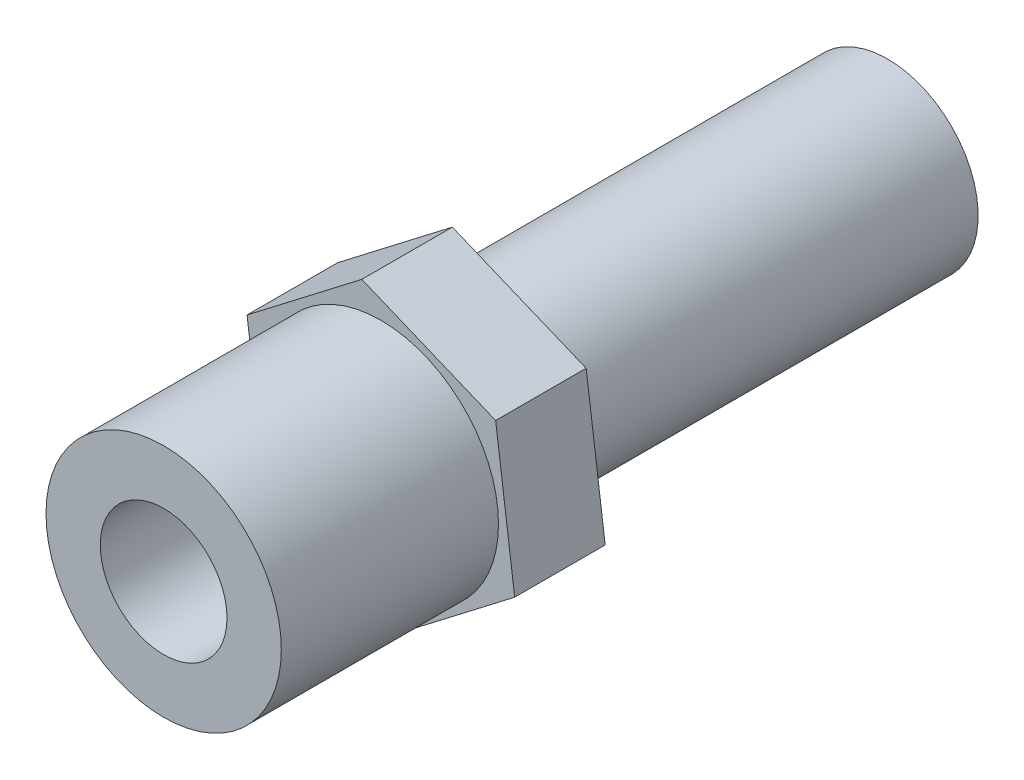
SolidWorks part; units mm, degrees
ref_plane "Front Plane" through (0, 0, 0) normal (0, 0, 1) x (1, 0, 0)
ref_plane "Top Plane" through (0, 0, 0) normal (0, 1, 0) x (1, 0, 0)
ref_plane "Right Plane" through (0, 0, 0) normal (1, 0, 0) x (0, 0, -1)
sketch "Sketch1" plane through (0, 0, 0) normal (0, 0, 1) x (1, 0, 0)
  circle A0 centre (0, 0) radius 6.5
  dimension "D1" = 6.5
extrude "Boss-Extrude1" add sketch "Sketch1" along normal blind 12
sketch "Sketch2" plane through (0, 0, 0) normal (0, 0, -1) x (-1, 0, 0)
  line L1 (-7.3935, -3.0555) -> (-1.0507, -7.9307)
  line L2 (-1.0507, -7.9307) -> (6.3429, -4.8753)
  line L3 (6.3429, -4.8753) -> (7.3935, 3.0555)
  line L4 (7.3935, 3.0555) -> (1.0507, 7.9307)
  line L5 (1.0507, 7.9307) -> (-6.3429, 4.8753)
  line L6 (-6.3429, 4.8753) -> (-7.3935, -3.0555)
  circle A0 centre (0, 0) radius 6.9282 construction
  dimension "D1" = 8
extrude "Boss-Extrude2" add sketch "Sketch2" along normal blind 5 contours L1 L2 L3 L4 L5 L6
sketch "Sketch3" plane through (0, 0, -5) normal (0, 0, -1) x (-1, 0, 0)
  line L0 (-7.3935, -3.0555) -> (7.3935, 3.0555)
  circle A0 centre (0, 0) radius 5
  dimension "D2" = 5
  dimension "D1" = 16
extrude "Boss-Extrude3" add sketch "Sketch3" along normal blind 23 contours L0 A0 | L0 A0
sketch "Sketch4" plane through (0, 0, 12) normal (0, 0, 1) x (1, 0, 0)
  circle A0 centre (0, 0) radius 3.5
  dimension "D1" = 3.5
extrude "Cut-Extrude1" cut sketch "Sketch4" against normal through all
